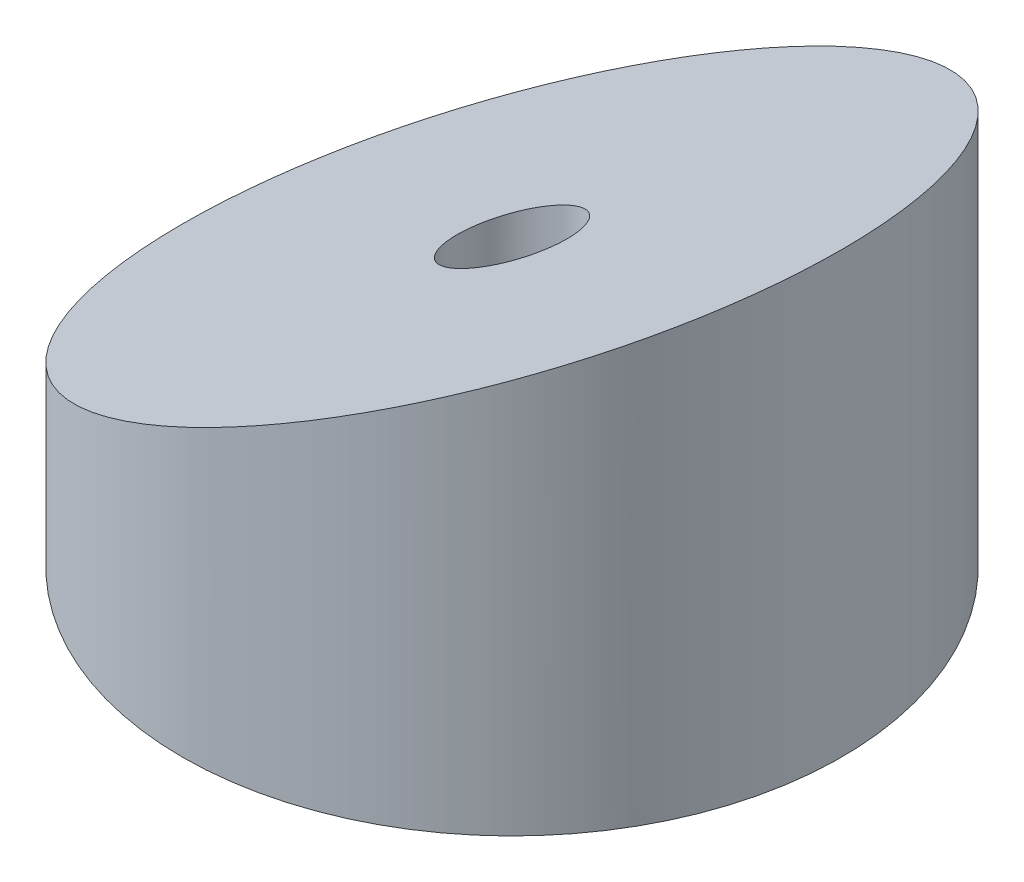
SolidWorks part; units mm, degrees
ref_plane "Front Plane" through (0, 0, 0) normal (0, 0, 1) x (1, 0, 0)
ref_plane "Top Plane" through (0, 0, 0) normal (0, 1, 0) x (1, 0, 0)
ref_plane "Right Plane" through (0, 0, 0) normal (1, 0, 0) x (0, 0, -1)
sketch "Sketch1" plane through (0, 0, 0) normal (0, 1, 0) x (1, 0, 0)
  circle A0 centre (0, 0) radius 120
  circle A1 centre (0, 0) radius 20
  dimension "D1" = 240
  dimension "D2" = 40
extrude "Boss-Extrude1" add sketch "Sketch1" along normal mid plane 160
sketch "Sketch2" plane through (0, 0, 0) normal (0, 0, 1) x (1, 0, 0)
  line L0 (-120, -31.9138) -> (-120, 80)
  line L1 (-120, 80) -> (-120, -80) construction
  line L2 (-120, 80) -> (120, 80)
  line L3 (120, 80) -> (-120, -31.9138)
  dimension "D1" = 25
extrude "Cut-Extrude1" cut sketch "Sketch2" against normal through all both and the other way through all contours L2 L3 L0
